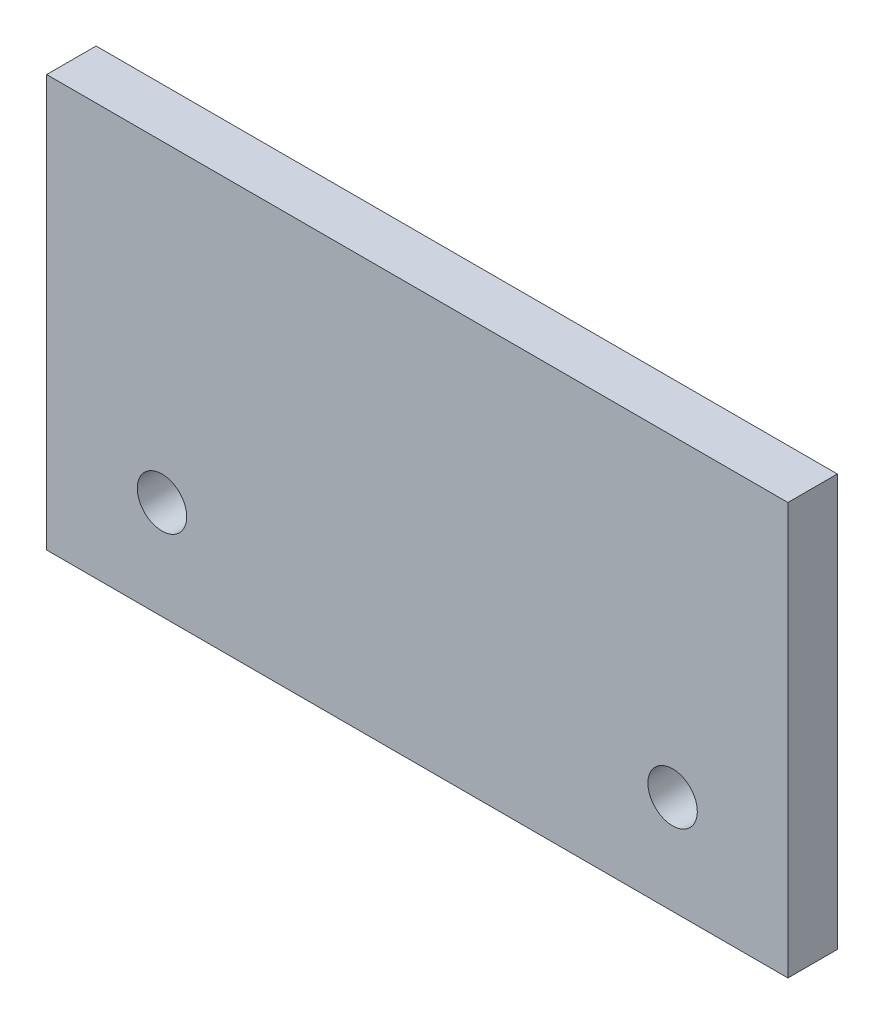
SolidWorks part; units mm, degrees
material "MDF"
ref_plane "Alzado" through (0, 0, 0) normal (0, 0, 1) x (1, 0, 0)
ref_plane "Planta" through (0, 0, 0) normal (0, 1, 0) x (1, 0, 0)
ref_plane "Vista lateral" through (0, 0, 0) normal (1, 0, 0) x (0, 0, -1)
sketch "Croquis1" plane through (0, 0, 0) normal (0, 0, 1) x (1, 0, 0)
  line L0 (0, 0) -> (0, 6.408) construction
  line L5 (-22.5, 12.5) -> (22.5, 12.5)
  line L6 (-22.5, 12.5) -> (-22.5, -12.5)
  line L7 (-22.5, -12.5) -> (22.5, -12.5)
  line L8 (22.5, 12.5) -> (22.5, -12.5)
  line L9 (-22.5, 12.5) -> (22.5, -12.5) construction
  line L10 (-22.5, -12.5) -> (22.5, 12.5) construction
  circle A0 centre (15.5, -6.5) radius 1.5
  circle A1 centre (-15.5, -6.5) radius 1.5
  point P0 (0, 0)
  dimension "D3" = 3
  dimension "D1" = 45
  dimension "D2" = 25
  dimension "D4" = 7
  dimension "D5" = 6
extrude "Saliente-Extruir1" add sketch "Croquis1" along normal blind 3
